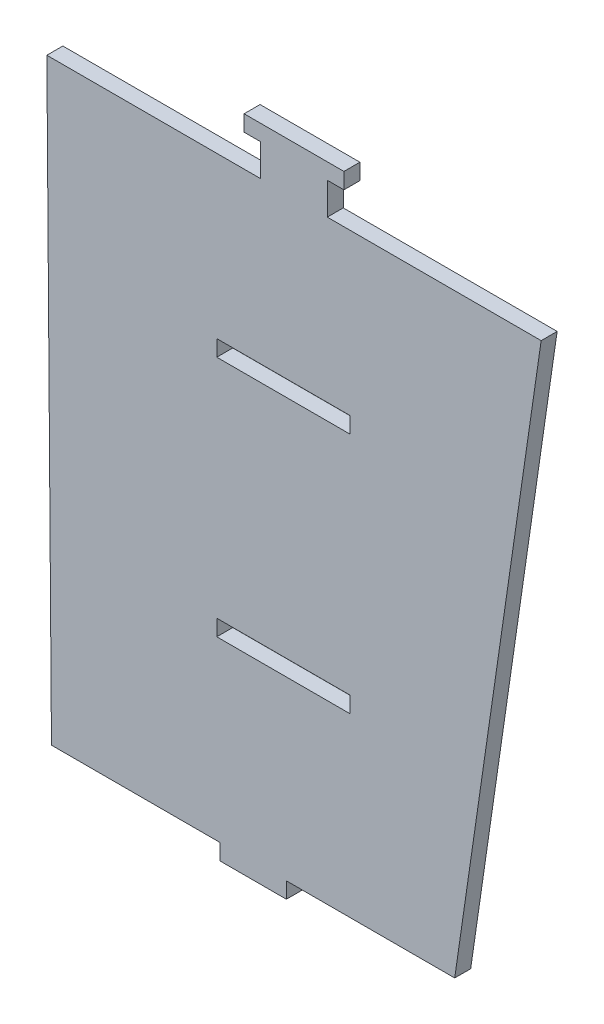
SolidWorks part; units mm, degrees
ref_plane "Front Plane" through (0, 0, 0) normal (0, 0, 1) x (1, 0, 0)
ref_plane "Top Plane" through (0, 0, 0) normal (0, 1, 0) x (1, 0, 0)
ref_plane "Right Plane" through (0, 0, 0) normal (1, 0, 0) x (0, 0, -1)
sketch "Sketch1" plane through (0, 0, 0) normal (0, 0, 1) x (1, 0, 0)
  line L0 (-102.4778, -1.524) -> (-110.7264, -58.3143)
  line L2 (-110.7264, -58.3143) -> (-126.7879, -58.3143)
  line L3 (-149.1994, -58.3143) -> (-149.6393, -1.524)
  line L4 (-149.6393, -1.524) -> (-129.2335, -1.524)
  line L5 (-126.0585, -1.524) -> (-126.0585, 1.524) construction
  line L6 (-133.1379, -58.3143) -> (-133.1379, -59.8383)
  line L7 (-126.7879, -58.3143) -> (-126.7879, -59.8383)
  line L8 (-122.8835, -1.524) -> (-122.8835, 1.524)
  line L9 (-133.1379, -59.8383) -> (-126.7879, -59.8383)
  line L10 (-133.1379, -58.3143) -> (-149.1994, -58.3143)
  line L11 (-129.2335, -1.524) -> (-129.2335, 1.524)
  line L12 (-129.2335, 1.524) -> (-130.821, 1.524)
  line L14 (-122.8835, -1.524) -> (-102.4778, -1.524)
  line L15 (-121.296, 1.524) -> (-121.296, 3.048)
  line L16 (-130.821, 1.524) -> (-130.821, 3.048)
  line L17 (-121.296, 1.524) -> (-122.8835, 1.524)
  line L18 (-121.296, 3.048) -> (-130.821, 3.048)
extrude "Boss-Extrude1" add sketch "Sketch1" along normal blind 1.524
sketch "Sketch2" plane through (0, 0, 1.524) normal (0, 0, 1) x (1, 0, 0)
  line L0 (-130.2538, -17.602) -> (-123.9038, -17.602) construction
  line L1 (-130.2538, -16.84) -> (-130.2538, -18.364) construction
  line L2 (-123.9038, -18.364) -> (-123.9038, -16.84) construction
  line L3 (-127.0788, -18.3709) -> (-127.0788, -16.8331) construction
  line L4 (-120.7288, -18.3709) -> (-120.7288, -16.8331)
  line L5 (-133.4288, -18.3709) -> (-133.4288, -16.8331)
  line L6 (-120.7288, -18.3709) -> (-133.4288, -18.3709)
  line L7 (-120.7288, -16.8331) -> (-133.4288, -16.8331)
  line L11 (-130.2538, -40.703) -> (-123.9038, -40.703) construction
  line L12 (-120.7288, -39.9342) -> (-133.4288, -39.9342)
  line L13 (-120.7288, -41.4719) -> (-120.7288, -39.9342)
  line L14 (-133.4288, -41.4719) -> (-133.4288, -39.9342)
  line L15 (-127.0788, -41.4719) -> (-127.0788, -39.9342) construction
  line L16 (-120.7288, -41.4719) -> (-133.4288, -41.4719)
extrude "Cut-Extrude1" cut sketch "Sketch2" against normal blind 1.524
